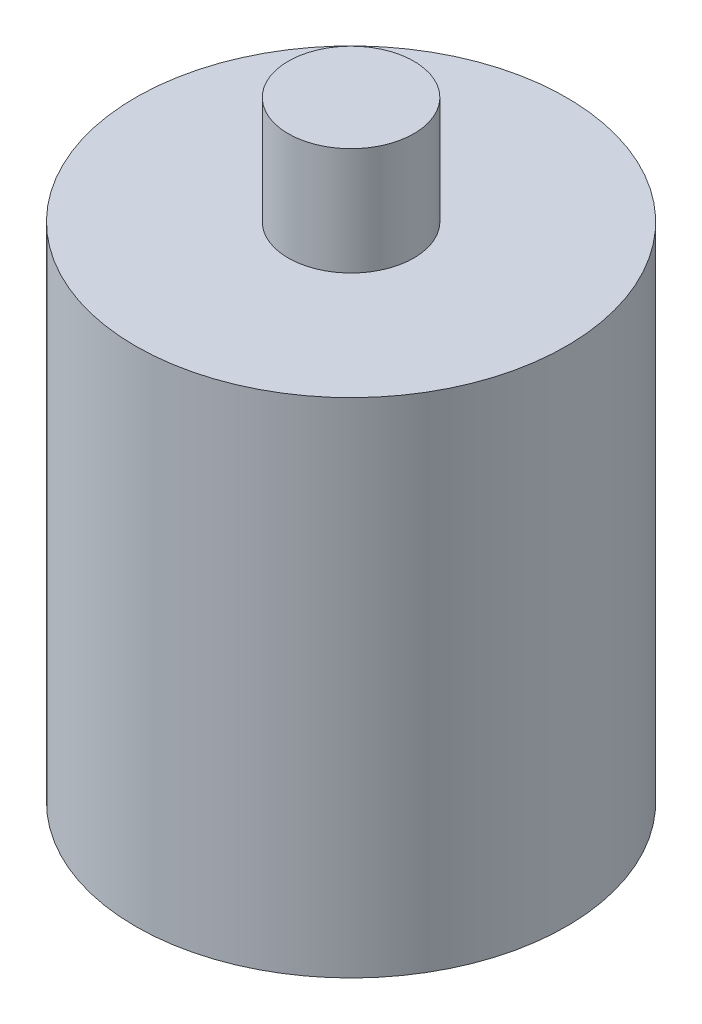
SolidWorks part; units mm, degrees
material "6061-T6 (SS)"
ref_plane "Front Plane" through (0, 0, 0) normal (0, 0, 1) x (1, 0, 0)
ref_plane "Top Plane" through (0, 0, 0) normal (0, 1, 0) x (1, 0, 0)
ref_plane "Right Plane" through (0, 0, 0) normal (1, 0, 0) x (0, 0, -1)
sketch "Sketch1" plane through (0, 0, 0) normal (0, 1, 0) x (1, 0, 0)
  circle A0 centre (0, 0) radius 6
  dimension "D1" = 12
extrude "Boss-Extrude1" add sketch "Sketch1" along normal blind 14
sketch "Sketch2" plane through (0, 14, 0) normal (0, 1, 0) x (1, 0, 0)
  circle A0 centre (0, 0) radius 1.75
  dimension "D1" = 3.5
extrude "Boss-Extrude2" add sketch "Sketch2" along normal blind 3
